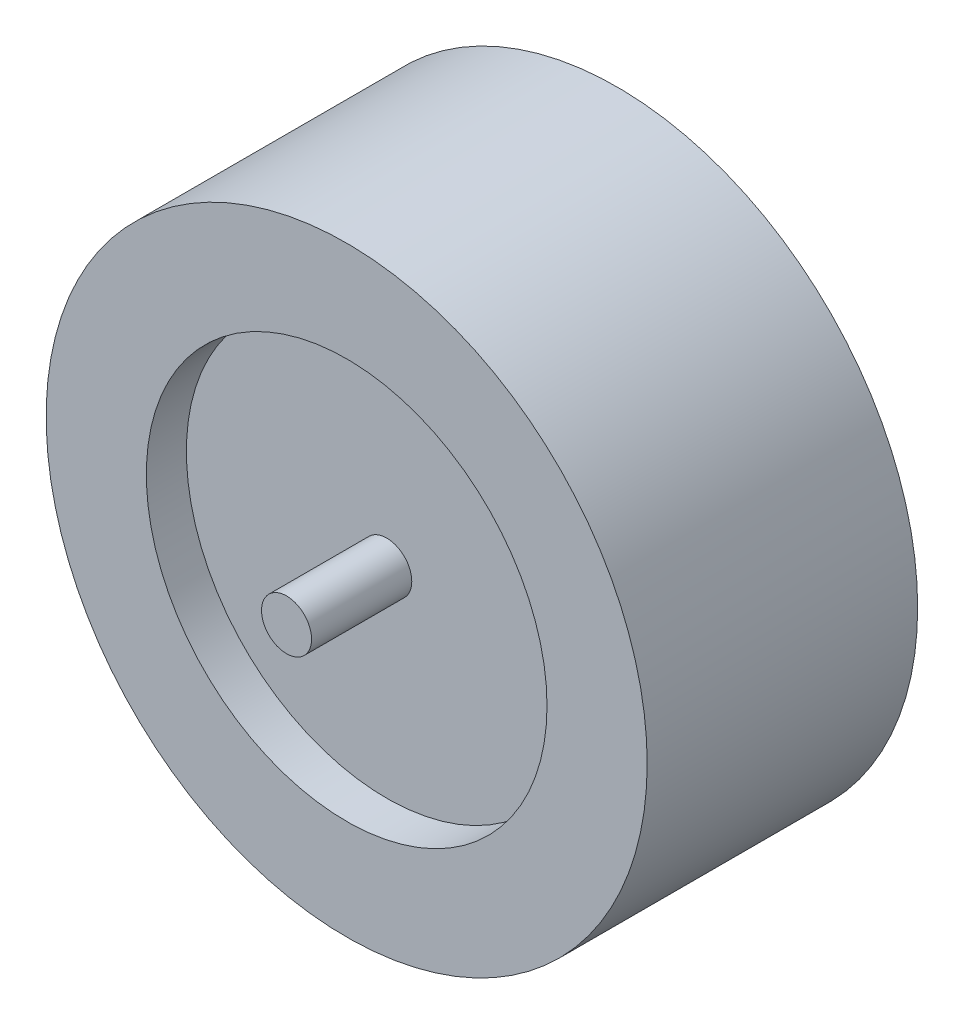
SolidWorks part; units mm, degrees
ref_plane "Front Plane" through (0, 0, 0) normal (0, 0, 1) x (1, 0, 0)
ref_plane "Top Plane" through (0, 0, 0) normal (0, 1, 0) x (1, 0, 0)
ref_plane "Right Plane" through (0, 0, 0) normal (1, 0, 0) x (0, 0, -1)
sketch "Sketch1" plane through (0, 0, 0) normal (0, 0, 1) x (1, 0, 0)
  circle A0 centre (0, 0) radius 30
  dimension "D1" = 60
extrude "Boss-Extrude1" add sketch "Sketch1" along normal blind 27
sketch "Sketch3" plane through (0, 0, 27) normal (0, 0, 1) x (1, 0, 0)
  circle A2 centre (0, 0) radius 20
  circle A3 centre (0, 0) radius 20
  dimension "D1" = 10
extrude "Cut-Extrude1" cut sketch "Sketch3" against normal blind 4
sketch "Sketch4" plane through (0, 0, 0) normal (0, 0, -1) x (-1, 0, 0)
  circle A2 centre (0, 0) radius 20
  circle A3 centre (0, 0) radius 20
  dimension "D1" = 10
extrude "Cut-Extrude2" cut sketch "Sketch4" against normal blind 4
sketch "Sketch5" plane through (0, 0, 23) normal (0, 0, 1) x (1, 0, 0)
  circle A0 centre (0, 0) radius 2.5
  dimension "D1" = 5
extrude "Boss-Extrude2" add sketch "Sketch5" along normal blind 10 and the other way blind 30
